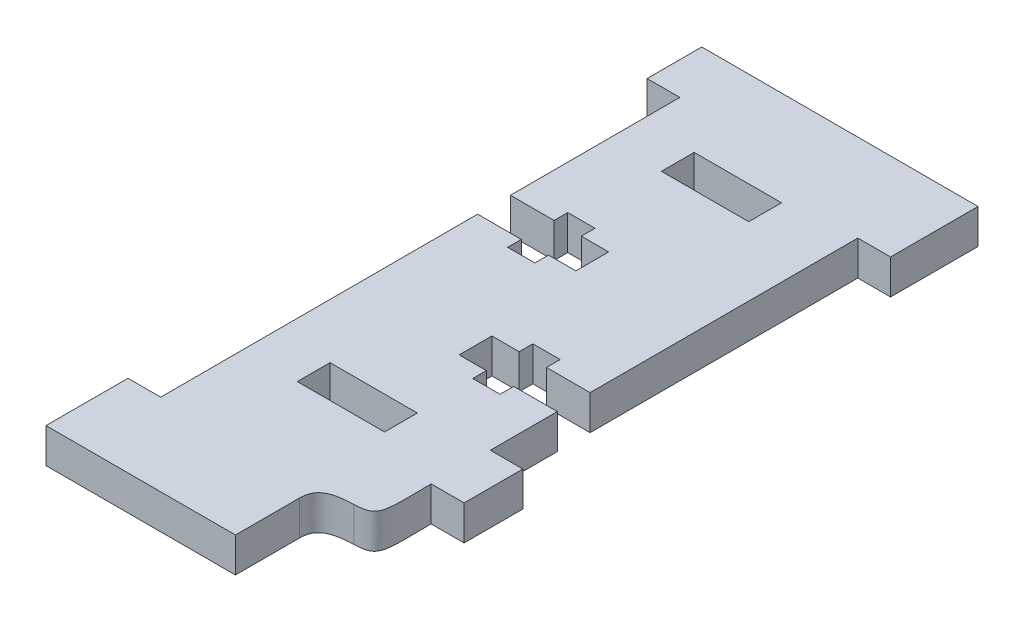
SolidWorks part; units mm, degrees
material "Acrylic (Medium-high impact)"
ref_plane "Front Plane" through (0, 0, 0) normal (0, 0, 1) x (1, 0, 0)
ref_plane "Top Plane" through (0, 0, 0) normal (0, 1, 0) x (1, 0, 0)
ref_plane "Right Plane" through (0, 0, 0) normal (1, 0, 0) x (0, 0, -1)
sketch "Sketch1" plane through (0, 0, 0) normal (0, 1, 0) x (1, 0, 0)
  line L2 (8.4508, -13.3816) -> (8.4069, -13.382)
  line L3 (8.4069, -13.382) -> (5.4327, -13.382)
  line L4 (5.4327, -13.382) -> (5.4765, -13.3816)
  line L5 (5.4765, -13.3816) -> (5.4765, -7.2515)
  line L6 (5.4765, -7.2515) -> (1.4836, -7.2515)
  line L7 (1.4836, -7.2515) -> (1.4836, -8.5015)
  line L8 (1.4836, -8.5015) -> (-1.012, -8.5015)
  line L9 (-1.012, -8.5015) -> (-1.012, -7.2515)
  line L10 (-1.012, -7.2515) -> (-3.5076, -7.2515)
  line L11 (-3.5076, -7.2515) -> (-3.5076, -4.2514)
  line L12 (-3.5076, -4.2514) -> (-1.012, -4.2514)
  line L13 (-1.012, -4.2514) -> (-1.012, -3.0013)
  line L14 (-1.012, -3.0013) -> (1.4836, -3.0013)
  line L15 (1.4836, -3.0013) -> (1.4836, -4.2514)
  line L16 (1.4836, -4.2514) -> (5.4765, -4.2514)
  line L17 (5.4765, -4.2514) -> (5.4765, 20.2464)
  line L18 (5.4765, 20.2464) -> (8.4712, 20.2464)
  line L19 (8.4712, 20.2464) -> (8.4712, 28.2467)
  line L20 (8.4712, 28.2467) -> (-16.8046, 28.2467)
  line L21 (-16.8046, 28.2467) -> (-16.8046, 23.2465)
  line L22 (-16.8046, 23.2465) -> (-13.8099, 23.2465)
  line L23 (-13.8099, 23.2465) -> (-13.8099, 7.746)
  line L24 (-13.8099, 7.746) -> (-9.817, 7.746)
  line L25 (-9.817, 7.746) -> (-9.817, 8.9961)
  line L26 (-9.817, 8.9961) -> (-7.3214, 8.9961)
  line L27 (-7.3214, 8.9961) -> (-7.3214, 7.746)
  line L28 (-7.3214, 7.746) -> (-4.8258, 7.746)
  line L29 (-4.8258, 7.746) -> (-4.8258, 4.7459)
  line L30 (-4.8258, 4.7459) -> (-7.3214, 4.7459)
  line L31 (-7.3214, 4.7459) -> (-7.3214, 3.4958)
  line L32 (-7.3214, 3.4958) -> (-9.817, 3.4958)
  line L33 (-9.817, 3.4958) -> (-9.817, 4.7459)
  line L34 (-9.817, 4.7459) -> (-13.8099, 4.7459)
  line L35 (-13.8099, 4.7459) -> (-13.8099, -24.2553)
  line L36 (-13.8099, -24.2553) -> (-16.8046, -24.2553)
  line L37 (-16.8046, -24.2553) -> (-16.8046, -31.7556)
  line L38 (-16.8046, -31.7556) -> (0.5295, -31.7556)
  line L39 (0.5295, -31.7556) -> (0.5295, -25.876)
  line L40 (8.4508, -18.7551) -> (8.4508, -13.3816)
  line L41 (-0.8123, 19.5486) -> (-0.8123, 16.5484)
  line L42 (-0.8123, 16.5484) -> (-8.7981, 16.5484)
  line L43 (-8.7981, 16.5484) -> (-8.7981, 19.5486)
  line L44 (-8.7981, 19.5486) -> (-0.8123, 19.5486)
  line L45 (-0.8123, -13.7721) -> (-0.8123, -16.7722)
  line L46 (-0.8123, -16.7722) -> (-8.7981, -16.7722)
  line L47 (-8.7981, -16.7722) -> (-8.7981, -13.7721)
  line L48 (-8.7981, -13.7721) -> (-0.8123, -13.7721)
  spline S2 degree 3 poles (0.5295, -25.876) (0.5295, -24.2161) (1.8842, -23.9808) (3.5436, -23.9159) knots 38 38 38 38 39 39 39 39
  spline S3 degree 3 poles (3.5436, -23.9159) (5.6513, -23.8333) (5.4823, -23.2775) (5.4327, -18.7551) knots 39 39 39 39 40 40 40 40
  spline S4 degree 3 poles (5.4327, -18.7551) (6.3246, -18.7551) (7.369, -18.7551) (8.4508, -18.7551) knots 40 40 40 40 41 41 41 41
extrude "Boss-Extrude1" add sketch "Sketch1" along normal blind 3.175
